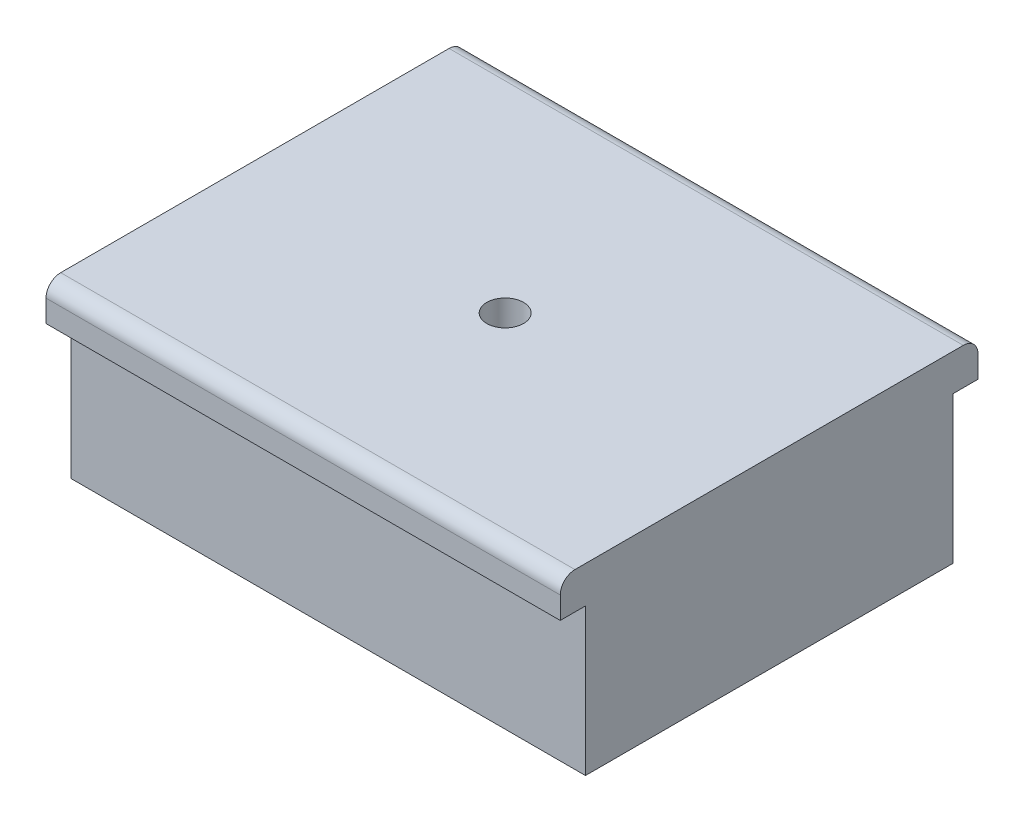
SolidWorks part; units mm, degrees
ref_plane "Front Plane" through (0, 0, 0) normal (0, 0, 1) x (1, 0, 0)
ref_plane "Top Plane" through (0, 0, 0) normal (0, 1, 0) x (1, 0, 0)
ref_plane "Right Plane" through (0, 0, 0) normal (1, 0, 0) x (0, 0, -1)
sketch "Sketch1" plane through (0, 0, 0) normal (1, 0, 0) x (0, 0, -1)
  line L0 (0, 0) -> (1270, 0)
  line L1 (1270, 0) -> (1270, 508)
  line L2 (1270, 508) -> (1357.1727, 508)
  line L3 (1357.1727, 508) -> (1357.1727, 584.2)
  line L4 (1306.3727, 635) -> (-36.3727, 635)
  line L5 (-87.1727, 584.2) -> (-87.1727, 508)
  line L6 (-87.1727, 508) -> (0, 508)
  line L7 (0, 508) -> (0, 0)
  arc A0 (1357.1727, 584.2) -> (1306.3727, 635) centre (1306.3727, 584.2) ccw
  arc A1 (-36.3727, 635) -> (-87.1727, 584.2) centre (-36.3727, 584.2) ccw
  point P11 (1357.1727, 635)
  point P14 (-87.1727, 635)
  dimension "D5" = 50.8
  dimension "D1" = 1270
  dimension "D2" = 508
  dimension "D3" = 127
  dimension "D4" = 127
extrude "Boss-Extrude1" add sketch "Sketch1" along normal blind 1778
sketch "Sketch2" plane through (0, 635, 0) normal (0, 1, 0) x (1, 0, 0)
  line L0 (1778, 1306.3727) -> (1778, -36.3727) construction
  line L1 (1778, -87.1727) -> (0, -87.1727) construction
  circle A0 centre (889, 611.3273) radius 63.5
  dimension "D1" = 127
  dimension "D2" = 889
  dimension "D3" = 698.5
extrude "Cut-Extrude1" cut sketch "Sketch2" against normal blind 1778
